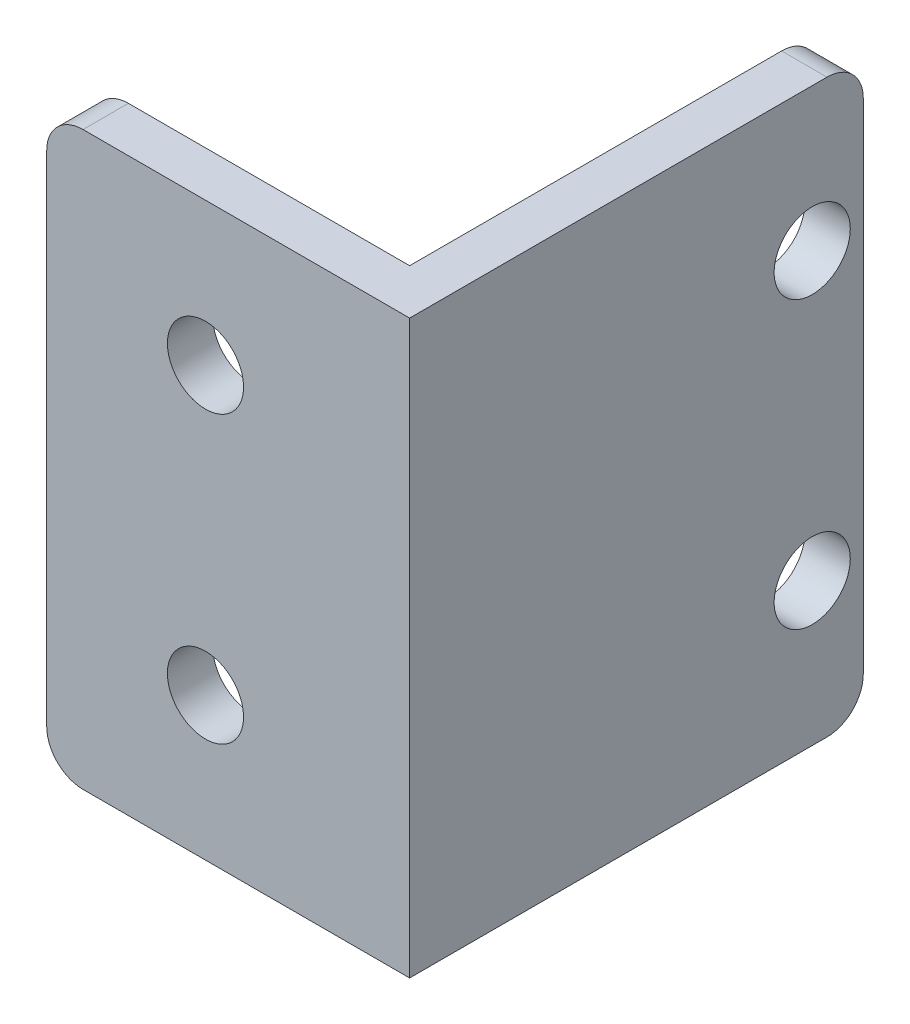
SolidWorks part; units mm, degrees
ref_plane "Front" through (0, 0, 0) normal (0, 0, 1) x (1, 0, 0)
ref_plane "Top" through (0, 0, 0) normal (0, 1, 0) x (1, 0, 0)
ref_plane "Right" through (0, 0, 0) normal (1, 0, 0) x (0, 0, -1)
sketch "Sketch1" plane through (0, 0, 0) normal (0, 1, 0) x (1, 0, 0)
  line L0 (0, 0) -> (-25.4, 0)
  line L1 (-25.4, 0) -> (-25.4, 3.175)
  line L2 (-25.4, 3.175) -> (-3.175, 3.175)
  line L3 (-3.175, 3.175) -> (-3.175, 31.75)
  line L4 (-3.175, 31.75) -> (0, 31.75)
  line L5 (0, 31.75) -> (0, 0)
  dimension "D1" = 3.175
  dimension "D2" = 25.4
  dimension "D3" = 31.75
extrude "Boss-Extrude1" add sketch "Sketch1" along normal blind 40
sketch "Sketch2" plane through (0, 0, -3.175) normal (0, 0, -1) x (-1, 0, 0)
  line L0 (14.2875, 40) -> (14.2875, 0) construction
  line L1 (3.175, 40) -> (25.4, 40) construction
  line L2 (3.175, 0) -> (25.4, 0) construction
  circle A0 centre (14.2875, 30) radius 2.665
  circle A1 centre (14.2875, 10) radius 2.665
  dimension "D1" = 5.33
  dimension "D2" = 10
  dimension "D3" = 10
extrude "Cut-Extrude1" cut sketch "Sketch2" against normal up to next
sketch "Sketch3" plane through (0, 0, 0) normal (1, 0, 0) x (0, 0, -1)
  circle A2 centre (28.1763, 10) radius 2.665
  circle A3 centre (28.1763, 30) radius 2.665
extrude "Cut-Extrude2" cut sketch "Sketch3" against normal up to next
fillet "Fillet1" radius 2.54 4 edges at (-25.4, 0, -1.5875) (-25.4, 40, -1.5875) (-1.5875, 40, -31.75) (-1.5875, 0, -31.75)
